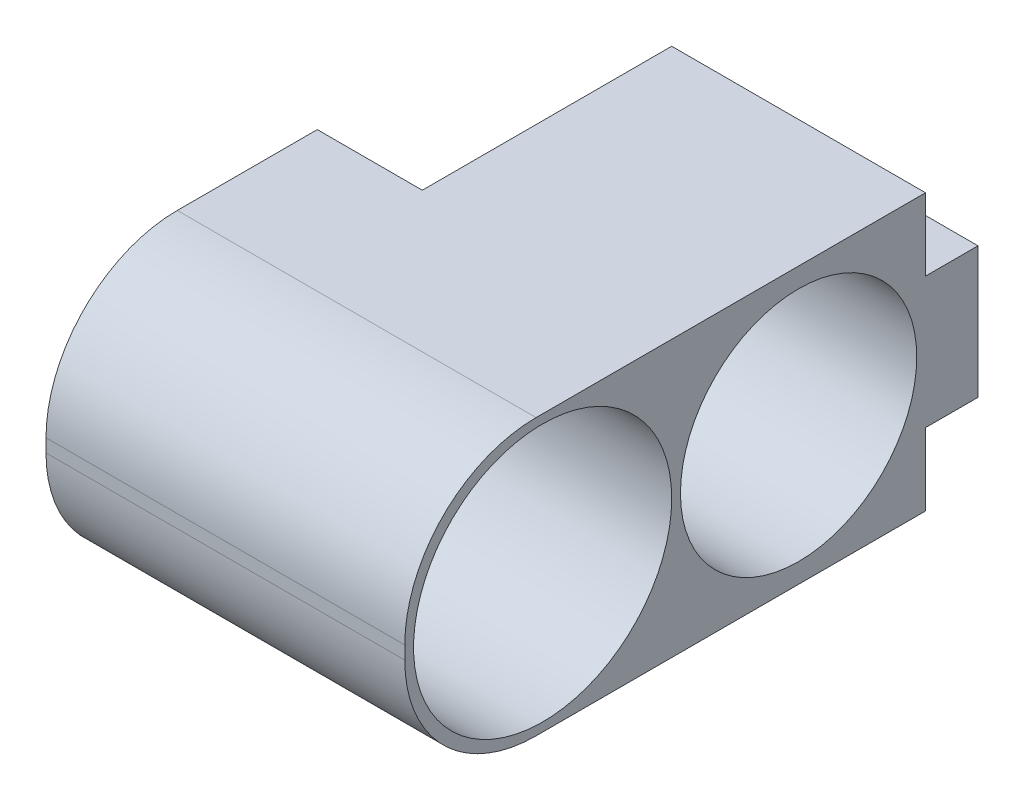
SolidWorks part; units mm, degrees
ref_plane "正面" through (0, 0, 0) normal (1, 0, 0) x (0, 1, 0)
ref_plane "平面" through (0, 0, 0) normal (0, 0, 1) x (0, 1, 0)
ref_plane "右側面" through (0, 0, 0) normal (0, 1, 0) x (-1, 0, 0)
sketch "ｽｹｯﾁ1" plane through (0, 0, 0) normal (1, 0, 0) x (0, 1, 0)
  line L0 (0, 0) -> (0, 12.857) construction
  line L1 (-3.15, 11.9) -> (3.15, 11.9)
  line L2 (-3.15, 11.9) -> (-3.15, 0)
  line L3 (-3.15, 0) -> (3.15, 0)
  line L4 (3.15, 11.9) -> (3.15, 0)
  line L6 (-1.5, 0) -> (1.5, 0)
  line L7 (-1.5, 0) -> (-1.5, -1.2)
  line L8 (-1.5, -1.2) -> (1.5, -1.2)
  line L9 (1.5, 0) -> (1.5, -1.2)
  line L10 (0, 0.2) -> (3.15, 0.2) construction
  line L11 (0, 5.6) -> (4.2836, 5.6) construction
  line L12 (0, 5.8) -> (3.15, 5.8) construction
  line L13 (0, 11.7) -> (4.2836, 11.7) construction
  line L14 (2.95, 8.75) -> (2.95, 11.9) construction
  circle A1 centre (0, 8.75) radius 2.95 construction
  circle A2 centre (0, 2.9) radius 2.7 construction
  point P4 (0, 0)
  point P12 (0, 0)
  dimension "D5" = 5.9
  dimension "D6" = 5.4
  dimension "D7" = 0.2
  dimension "D8" = 0.2
  dimension "D1" = 0.2
  dimension "D2" = 1.2
  dimension "D3" = 3
  dimension "D9" = 0.2
extrude "ﾎﾞｽ - 押し出し2" add sketch "ｽｹｯﾁ1" against normal blind 3 contours L3 L4 L1 L2 | L7 L8 L9 L6
sketch "ｽｹｯﾁ7" plane through (-3, 0, 0) normal (-1, 0, 0) x (0, -1, 0)
  line L0 (3.15, 11.9) -> (3.15, 0) construction
  line L1 (-3.15, 0) -> (3.15, 0)
  line L2 (-3.15, 0) -> (-3.15, 5.7)
  line L3 (-3.15, 5.7) -> (3.15, 5.7)
  line L4 (3.15, 0) -> (3.15, 5.7)
  dimension "D1" = 5.7
extrude "ﾎﾞｽ - 押し出し4" add sketch "ｽｹｯﾁ7" along normal blind 2.8
sketch "ｽｹｯﾁ8" plane through (-3, 0, 0) normal (-1, 0, 0) x (0, -1, 0)
  line L1 (-3.15, 11.9) -> (3.15, 11.9)
  line L2 (-3.15, 11.9) -> (-3.15, 5.7)
  line L3 (-3.15, 5.7) -> (3.15, 5.7)
  line L4 (3.15, 11.9) -> (3.15, 5.7)
extrude "ﾎﾞｽ - 押し出し5" add sketch "ｽｹｯﾁ8" along normal blind 5.2
sketch "ｽｹｯﾁ5" plane through (0, 0, 0) normal (1, 0, 0) x (0, 1, 0)
  line L0 (0, 0) -> (0, 11.6387) construction
  line L1 (0, 0.2) -> (3.15, 0.2) construction
  line L2 (3.15, 11.9) -> (3.15, 0) construction
  line L3 (1.5, 0) -> (3.15, 0) construction
  line L4 (0, 5.6) -> (3.15, 5.6) construction
  line L5 (0, 5.8) -> (3.15, 5.8) construction
  circle A0 centre (0, 2.9) radius 2.7
  circle A1 centre (0, 8.75) radius 2.95
  dimension "D1" = 5.4
  dimension "D3" = 5.9
  dimension "D2" = 0.2
  dimension "D4" = 0.2
extrude "ｶｯﾄ - 押し出し3" cut sketch "ｽｹｯﾁ5" against normal through all
fillet "ﾌｨﾚｯﾄ1" radius 3 2 edges at (-4.1, 3.15, 11.9) (-4.1, -3.15, 11.9)
